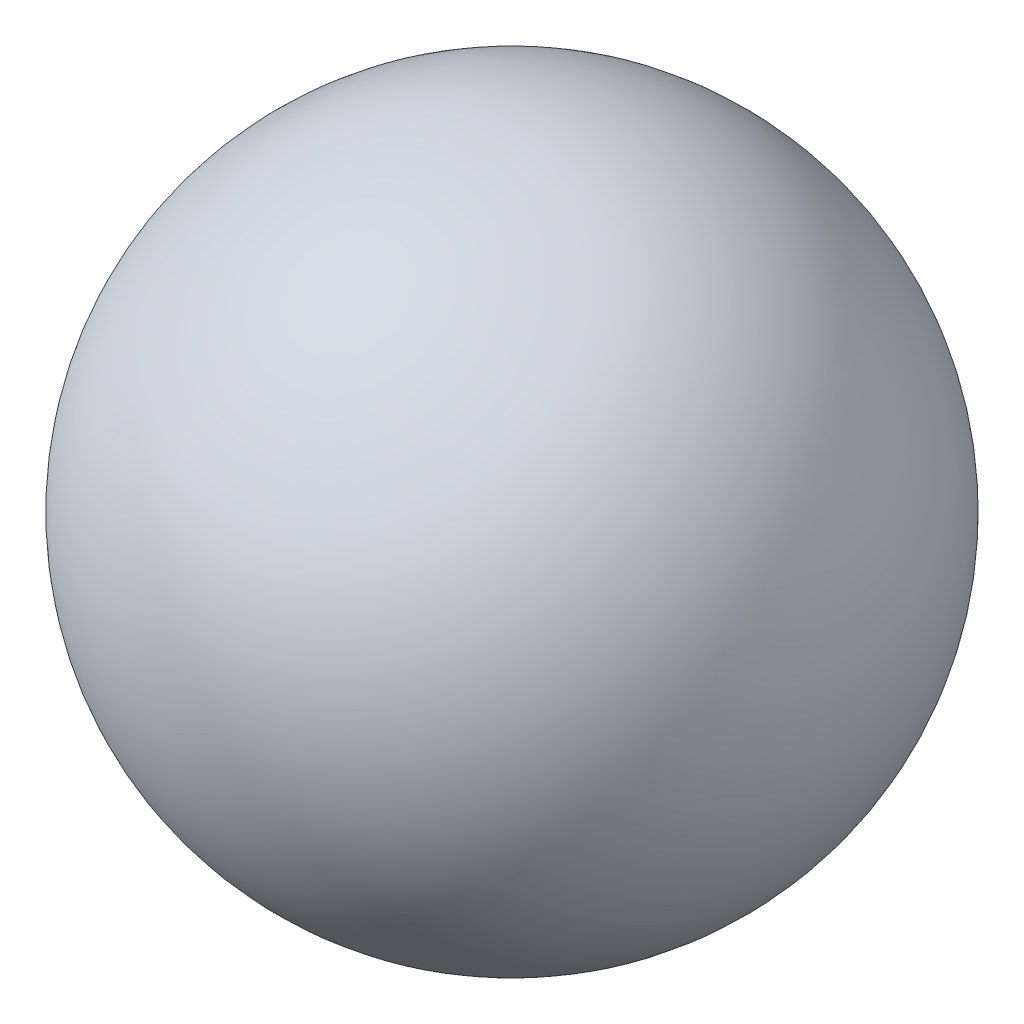
SolidWorks part; units mm, degrees
material "Ti-6Al-2Sn-2Zr-2Mo-2Cr-0.25Si (SS)"
ref_plane "Front Plane" through (0, 0, 0) normal (0, 0, 1) x (1, 0, 0)
ref_plane "Top Plane" through (0, 0, 0) normal (0, 1, 0) x (1, 0, 0)
ref_plane "Right Plane" through (0, 0, 0) normal (1, 0, 0) x (0, 0, -1)
sketch "Sketch2" plane through (0, 0, 0) normal (0, 0, 1) x (1, 0, 0)
  line L0 (0, 420) -> (0, 416.14)
  line L1 (0, -420) -> (0, -416.14)
  arc A0 (0, 420) -> (0, -420) centre (0, 0) ccw
  arc A1 (0, 416.14) -> (0, -416.14) centre (0, 0) ccw
revolve "Revolve6" add sketch "Sketch2" angle 360 about L1
